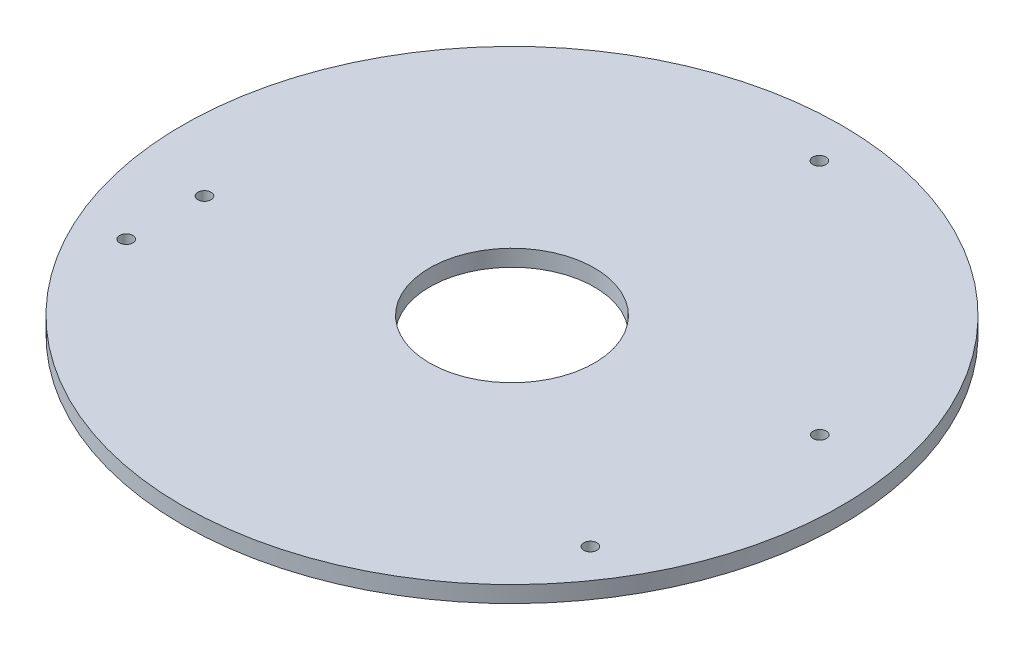
SolidWorks part; units mm, degrees
ref_plane "前视基准面" through (0, 0, 0) normal (0, 0, 1) x (1, 0, 0)
ref_plane "上视基准面" through (0, 0, 0) normal (0, 1, 0) x (1, 0, 0)
ref_plane "右视基准面" through (0, 0, 0) normal (1, 0, 0) x (0, 0, -1)
sketch "草图1" plane through (0, 0, 0) normal (0, 1, 0) x (1, 0, 0)
  circle A0 centre (0, 0) radius 80
  circle A1 centre (4.7844, 69.8363) radius 1.6
  circle A2 centre (-62.8722, -30.7747) radius 1.6
  circle A3 centre (58.0878, -39.0616) radius 1.6
  dimension "D1" = 160
extrude "凸台-拉伸1" add sketch "草图1" along normal blind 4
sketch "草图2" plane through (0, 4, 0) normal (0, 1, 0) x (1, 0, 0)
  line L0 (-69.3905, -13.5613) -> (-13.5882, 69.4212)
  line L1 (-13.5882, 69.4212) -> (69.3944, 13.6189)
  line L2 (69.3944, 13.6189) -> (13.5921, -69.3636)
  line L3 (13.5921, -69.3636) -> (-69.3905, -13.5613)
  line L4 (-69.3905, -13.5613) -> (69.3944, 13.6189) construction
  line L5 (-13.5882, 69.4212) -> (13.5921, -69.3636) construction
  line L6 (-62.8722, -30.7747) -> (4.7844, 69.8363) construction
  circle A0 centre (-62.4512, -12.2023) radius 1.6
  circle A1 centre (62.4551, 12.2599) radius 1.6
  point P12 (0.0019, 0.0288)
  dimension "D3" = 3.2
  dimension "D4" = 3.2
  dimension "D5" = 5
  dimension "D6" = 5
  dimension "D1" = 100
  dimension "D2" = 100
extrude "切除-拉伸1" cut sketch "草图2" against normal through all both and the other way through all contours A0 | A1
sketch "草图3" plane through (0, 4, 0) normal (0, 1, 0) x (1, 0, 0)
  circle A0 centre (0, 0) radius 20
  dimension "D1" = 40
extrude "切除-拉伸2" cut sketch "草图3" against normal through all both and the other way through all
